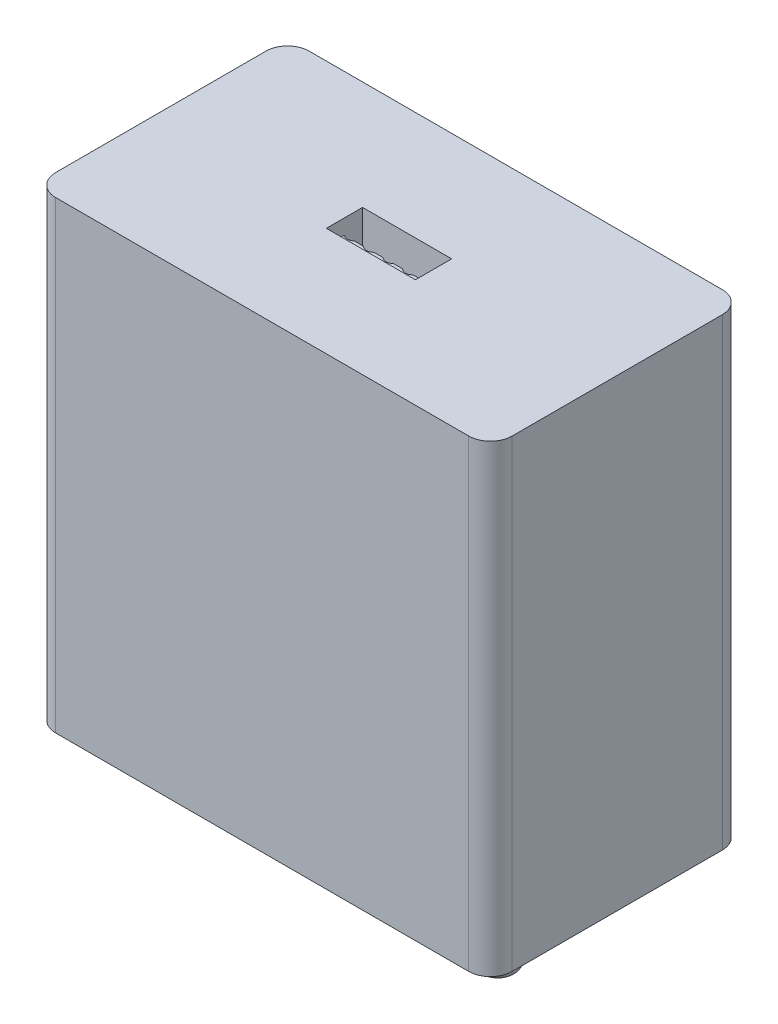
SolidWorks part; units mm, degrees
material "ABS"
ref_plane "Front Plane" through (0, 0, 0) normal (0, 0, 1) x (1, 0, 0)
ref_plane "Top Plane" through (0, 0, 0) normal (0, 1, 0) x (1, 0, 0)
ref_plane "Right Plane" through (0, 0, 0) normal (1, 0, 0) x (0, 0, -1)
sketch "Sketch1" plane through (0, 0, 0) normal (0, 1, 0) x (1, 0, 0)
  line L1 (-31.5, -17.5) -> (31.5, -17.5)
  line L2 (-31.5, -17.5) -> (-31.5, 17.5)
  line L3 (-31.5, 17.5) -> (31.5, 17.5)
  line L4 (31.5, -17.5) -> (31.5, 17.5)
  line L5 (-31.5, -17.5) -> (31.5, 17.5) construction
  line L6 (-31.5, 17.5) -> (31.5, -17.5) construction
  point P0 (0, 0)
  dimension "D1" = 63
  dimension "D2" = 35
extrude "Boss-Extrude1" add sketch "Sketch1" along normal blind 64
fillet "Fillet1" radius 3 4 edges at (-31.5, 32, 17.5) (-31.5, 32, -17.5) (31.5, 32, -17.5) (31.5, 32, 17.5)
sketch "Sketch2" plane through (0, 0, 0) normal (0, -1, 0) x (1, 0, 0)
  line L0 (0, 0) -> (0, 10.6641) construction
  circle A0 centre (-15, 0) radius 2.5
  circle A1 centre (15, 0) radius 2.5
  dimension "D1" = 5
  dimension "D2" = 15
extrude "Boss-Extrude2" add sketch "Sketch2" along normal blind 15
fillet "Fillet2" radius 1 2 edges at (-15, -15, -2.5) (15, -15, 2.5)
sketch "Sketch4" plane through (0, 0, 0) normal (0, -1, 0) x (1, 0, 0)
  circle A0 centre (0, 0) radius 0.5
  dimension "D1" = 1
extrude "Cut-Extrude1" cut sketch "Sketch4" against normal blind 1 contours A0
sketch "Sketch5" plane through (0, 64, 0) normal (0, 1, 0) x (1, 0, 0)
  line L1 (-6.15, 2.5) -> (6.15, 2.5)
  line L2 (-6.15, 2.5) -> (-6.15, -2.5)
  line L3 (-6.15, -2.5) -> (6.15, -2.5)
  line L4 (6.15, 2.5) -> (6.15, -2.5)
  line L5 (-6.15, 2.5) -> (6.15, -2.5) construction
  line L6 (-6.15, -2.5) -> (6.15, 2.5) construction
  point P0 (0, 0)
  dimension "D1" = 12.3
  dimension "D2" = 5
extrude "Cut-Extrude2" cut sketch "Sketch5" against normal blind 13
sketch "Sketch6" plane through (0, 51, 0) normal (0, 1, 0) x (1, 0, 0)
  line L9 (-6.07, -0.08) -> (-6.07, -2.42)
  line L10 (-6.07, -2.42) -> (6.07, -2.42)
  line L11 (6.07, -0.08) -> (6.07, -2.42)
  line L13 (3.4216, -0.08) -> (4.619, -0.08)
  line L14 (0.7216, -0.08) -> (1.95, -0.08)
  line L15 (-1.9784, -0.08) -> (-0.75, -0.08)
  line L16 (-4.6784, -0.08) -> (-3.45, -0.08)
  spline S10 degree 2 poles (6.07, -0.08) (5.376, -0.6569) (4.619, -0.08) knots 0.014709 0.014709 0.014709 0.930781 0.930781 0.930781
  spline S11 degree 2 poles (3.4216, -0.08) (2.6955, -0.7014) (1.95, -0.08) knots 0.014709 0.014709 0.014709 0.984687 0.984687 0.984687
  spline S12 degree 2 poles (0.7216, -0.08) (-0.0045, -0.7014) (-0.75, -0.08) knots 0.014709 0.014709 0.014709 0.984687 0.984687 0.984687
  spline S13 degree 2 poles (-1.9784, -0.08) (-2.7045, -0.7014) (-3.45, -0.08) knots 0.014709 0.014709 0.014709 0.984687 0.984687 0.984687
  spline S14 degree 2 poles (-4.6784, -0.08) (-5.3935, -0.6248) (-6.07, -0.08) knots 0.084891 0.084891 0.084891 0.984687 0.984687 0.984687
  point P8 (0, 0)
  point P10 (-6.15, 0)
extrude "Boss-Extrude3" add sketch "Sketch6" along normal blind 11
sketch "Sketch7" plane through (0, 0, 17.5) normal (0, 0, 1) x (1, 0, 0)
  line L0 (-21.6768, 2.6436) -> (-21.6768, 22.4042)
  text T0 "67W" font "Century Schoolbook" height 3.5
